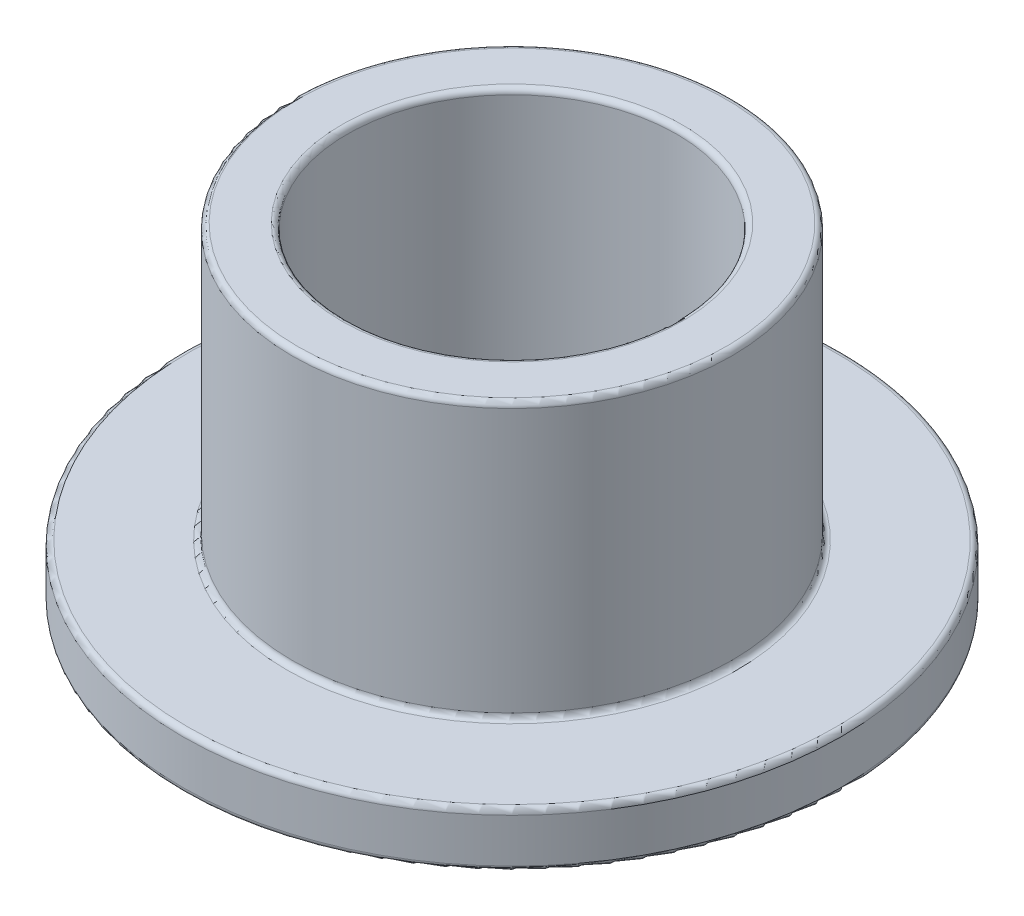
SolidWorks part; units mm, degrees
ref_plane "Front" through (0, 0, 0) normal (0, 0, 1) x (1, 0, 0)
ref_plane "Top" through (0, 0, 0) normal (0, 1, 0) x (1, 0, 0)
ref_plane "Right" through (0, 0, 0) normal (1, 0, 0) x (0, 0, -1)
sketch "Sketch1" plane through (0, 0, 0) normal (0, 1, 0) x (1, 0, 0)
  circle A0 centre (0, 0) radius 3
  circle A1 centre (0, 0) radius 4
  circle A2 centre (0, 0) radius 6
  dimension "ID" = 6
  dimension "OD" = 8
  dimension "FlangeOD" = 12
sketch "Sketch2" plane through (0, 0, 0) normal (1, 0, 0) x (0, 0, -1)
  line L0 (6, 0) -> (6, 1) construction
  line L1 (-4, 0) -> (-4, 6) construction
  line L8 (0, 0) -> (0, 6) construction
  point P5 (-6, 0)
  dimension "Flange Thickness" = 1
  dimension "Length" = 6
sketch "Sketch3" plane through (0, 0, 0) normal (0, 1, 0) x (1, 0, 0)
  circle A0 centre (0, 0) radius 3 construction
  circle A1 centre (0, 0) radius 4 construction
  circle A2 centre (0, 0) radius 3
  circle A3 centre (0, 0) radius 4
extrude "Boss-Extrude1" add sketch "Sketch3" along normal up to vertex (6 mm away) up to point (0, 6, 4)
sketch "Sketch4" plane through (0, 0, 0) normal (0, 1, 0) x (1, 0, 0)
  circle A0 centre (0, 0) radius 6 construction
  circle A1 centre (0, 0) radius 4 construction
  circle A2 centre (0, 0) radius 6
  circle A3 centre (0, 0) radius 4
extrude "Boss-Extrude2" add sketch "Sketch4" along normal up to vertex (1 mm away) up to point (0, 1, -6)
fillet "Fillet1" radius 0.1 6 edges at (0, 0, 3) (0, 0, 6) (0, 1, 4) (0, 1, 6) (0, 6, 3) (0, 6, 4)
equation "\"D1@Fillet1\"=(\"OD@Sketch1\"-\"ID@Sketch1\")*.05"
